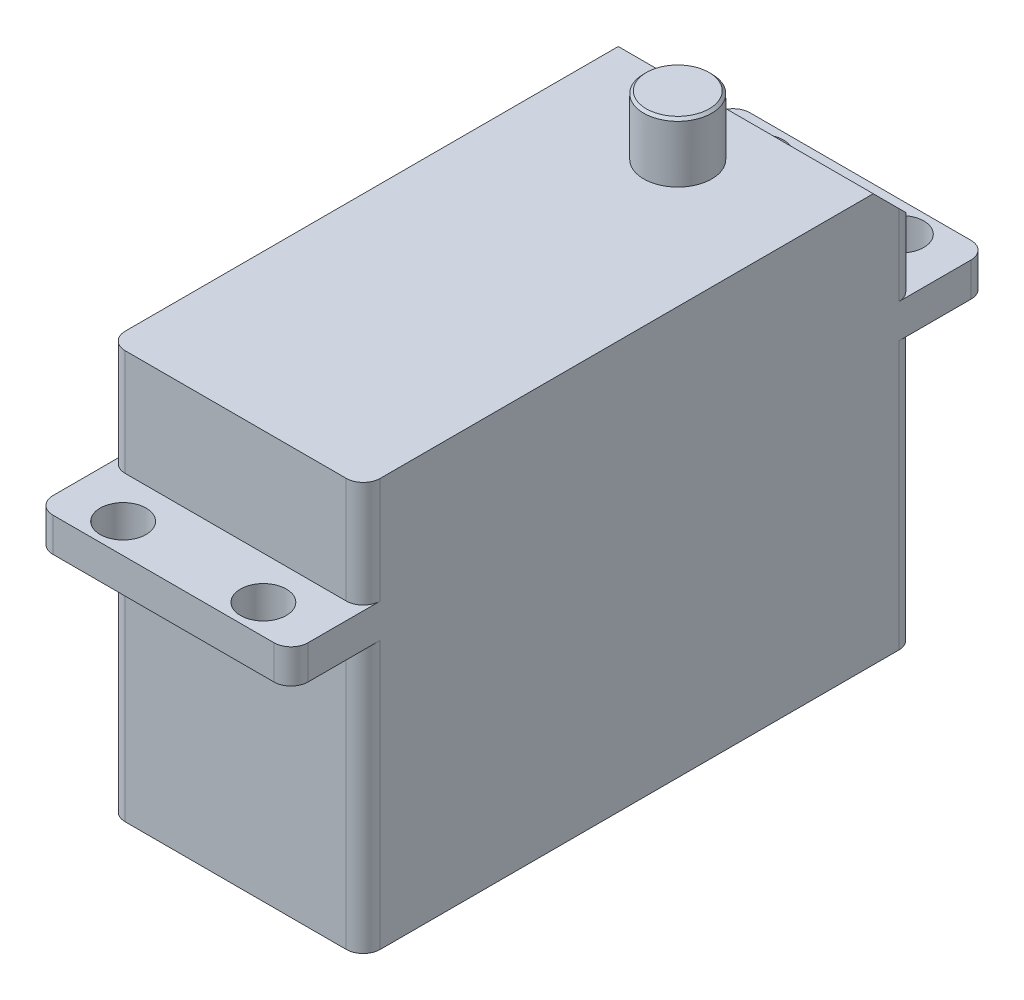
SolidWorks part; units mm, degrees
ref_plane "前视基准面" through (0, 0, 0) normal (0, 0, 1) x (1, 0, 0)
ref_plane "上视基准面" through (0, 0, 0) normal (0, 1, 0) x (1, 0, 0)
ref_plane "右视基准面" through (0, 0, 0) normal (1, 0, 0) x (0, 0, -1)
sketch "草图1" plane through (0, 0, 0) normal (0, 1, 0) x (1, 0, 0)
  line L1 (-15, -32.5) -> (15, -32.5)
  line L2 (-15, -32.5) -> (-15, 32.5)
  line L3 (-15, 32.5) -> (15, 32.5)
  line L4 (15, -32.5) -> (15, 32.5)
  line L5 (-15, -32.5) -> (15, 32.5) construction
  line L6 (-15, 32.5) -> (15, -32.5) construction
  point P0 (0, 0)
  dimension "D1" = 30
  dimension "D2" = 65
extrude "凸台-拉伸1" add sketch "草图1" along normal blind 48
ref_plane "基准面1" through (0, 35.5, 0) normal (0, -1, 0) x (-1, 0, 0)
sketch "草图2" plane through (0, 35.5, 0) normal (0, -1, 0) x (-1, 0, 0)
  line L1 (15, -41) -> (-15, -41)
  line L2 (15, -41) -> (15, 41)
  line L3 (15, 41) -> (-15, 41)
  line L4 (-15, -41) -> (-15, 41)
  line L5 (15, -41) -> (-15, 41) construction
  line L6 (15, 41) -> (-15, -41) construction
  point P0 (0, 0)
  dimension "D1" = 82
  dimension "D2" = 30
extrude "凸台-拉伸2" add sketch "草图2" along normal blind 4
sketch "草图3" plane through (0, 35.5, 0) normal (0, 1, 0) x (1, 0, 0)
  line L1 (-8.25, -37.5) -> (8.25, -37.5) construction
  line L2 (-8.25, -37.5) -> (-8.25, 37.5) construction
  line L3 (-8.25, 37.5) -> (8.25, 37.5) construction
  line L4 (8.25, -37.5) -> (8.25, 37.5) construction
  line L5 (-8.25, -37.5) -> (8.25, 37.5) construction
  line L6 (-8.25, 37.5) -> (8.25, -37.5) construction
  circle A0 centre (-8.25, 37.5) radius 2.7
  circle A1 centre (8.25, 37.5) radius 2.7
  circle A2 centre (8.25, -37.5) radius 2.7
  circle A3 centre (-8.25, -37.5) radius 2.7
  point P0 (0, 0)
  dimension "D1" = 5.4
  dimension "D2" = 75
  dimension "D3" = 16.5
extrude "切除-拉伸1" cut sketch "草图3" against normal blind 4
sketch "草图4" plane through (0, 48, 0) normal (0, 1, 0) x (1, 0, 0)
  line L0 (-15, 32.5) -> (15, 32.5) construction
  circle A0 centre (0, 19.5) radius 4
  dimension "D1" = 8
  dimension "D2" = 13
extrude "凸台-拉伸3" add sketch "草图4" along normal blind 7
chamfer "倒角1" distance 0.3 angle 45 1 edges at (0, 55, -15.5)
fillet "圆角1" radius 2 6 edges at (15, 41.75, 32.5) (-15, 41.75, 32.5) (-15, 15.75, 32.5) (15, 15.75, 32.5) (15, 15.75, -32.5) (-15, 15.75, -32.5)
chamfer "倒角2" distance 5 angle 45 1 edges at (0, 48, -32.5)
fillet "圆角2" radius 2 6 edges at (-15, 33.5, 41) (15, 33.5, 41) (-15, 33.5, -41) (15, 33.5, -41) (15, 39.25, -32.5) (-15, 39.25, -32.5)
